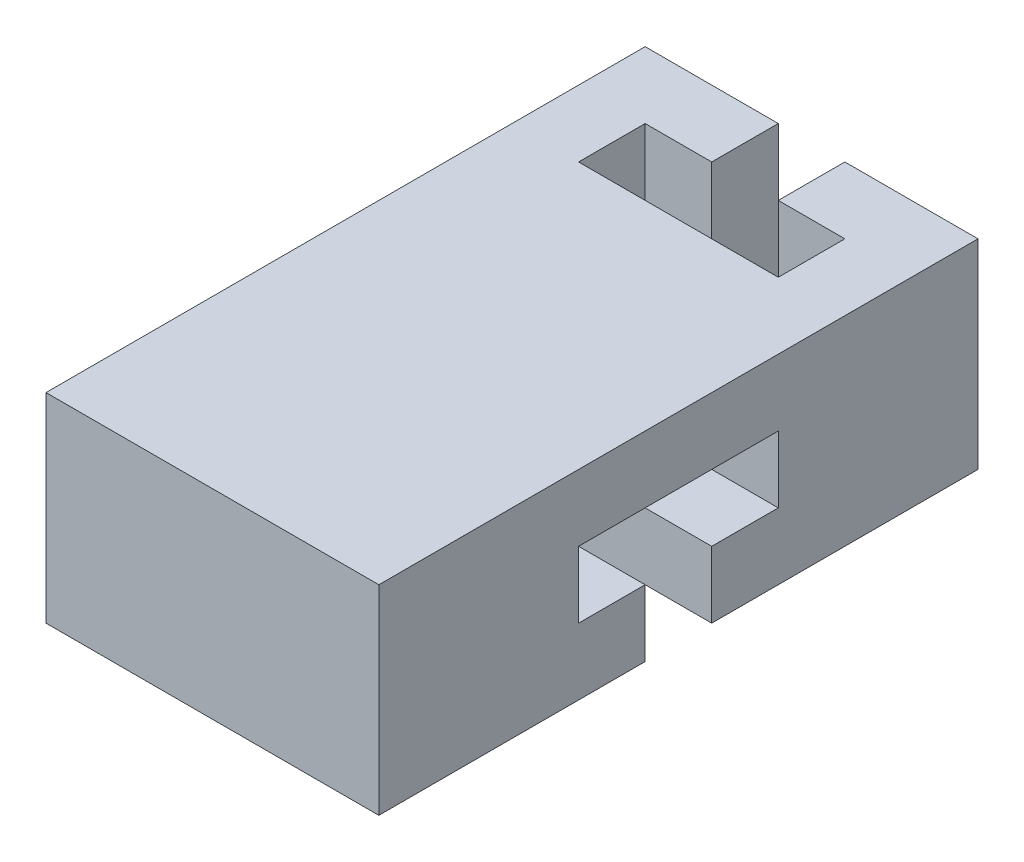
SolidWorks part; units mm, degrees
ref_plane "Front Plane" through (0, 0, 0) normal (0, 0, 1) x (1, 0, 0)
ref_plane "Top Plane" through (0, 0, 0) normal (0, 1, 0) x (1, 0, 0)
ref_plane "Right Plane" through (0, 0, 0) normal (1, 0, 0) x (0, 0, -1)
other "Center of Mass"
sketch "Sketch2" plane through (0, 0, 0) normal (1, 0, 0) x (0, 0, -1)
  line L0 (-25, -75) -> (-25, -25)
  line L1 (-225, 75) -> (225, 75)
  line L2 (-225, 75) -> (-225, -75)
  line L3 (-225, -75) -> (-25, -75)
  line L4 (225, 75) -> (225, -75)
  line L5 (-225, 75) -> (225, -75) construction
  line L6 (-225, -75) -> (225, 75) construction
  line L7 (-25, -25) -> (-75, -25)
  line L8 (-75, -25) -> (-75, 25)
  line L9 (-75, 25) -> (75, 25)
  line L10 (75, 25) -> (75, -25)
  line L11 (75, -25) -> (25, -25)
  line L12 (25, -25) -> (25, -75)
  line L13 (25, -75) -> (225, -75)
  point P0 (0, 0)
  point P21 (75, 0)
  dimension "D1" = 450
  dimension "D2" = 150
  dimension "D3" = 50
  dimension "D4" = 50
  dimension "D5" = 100
  dimension "D6" = 50
  dimension "D7" = 150
  dimension "D8" = 50
extrude "Boss-Extrude1" add sketch "Sketch2" against normal blind 250
sketch "Sketch3" plane through (0, 75, 0) normal (0, 1, 0) x (1, 0, 0)
  line L0 (-100, 225) -> (-100, 175)
  line L1 (-250, 225) -> (0, 225) construction
  line L2 (-100, 175) -> (-50, 175)
  line L3 (-50, 175) -> (-50, 125)
  line L4 (-50, 125) -> (-200, 125)
  line L5 (-200, 125) -> (-200, 175)
  line L6 (-200, 175) -> (-150, 175)
  line L7 (-150, 175) -> (-150, 225)
  line L8 (-150, 225) -> (-100, 225)
  line L9 (0, 225) -> (0, -225) construction
  line L10 (-250, 225) -> (-250, -225) construction
  dimension "D1" = 50
  dimension "D2" = 50
  dimension "D3" = 50
  dimension "D4" = 50
  dimension "D5" = 50
  dimension "D6" = 50
  dimension "D7" = 50
extrude "Cut-Extrude1" cut sketch "Sketch3" against normal blind 250
